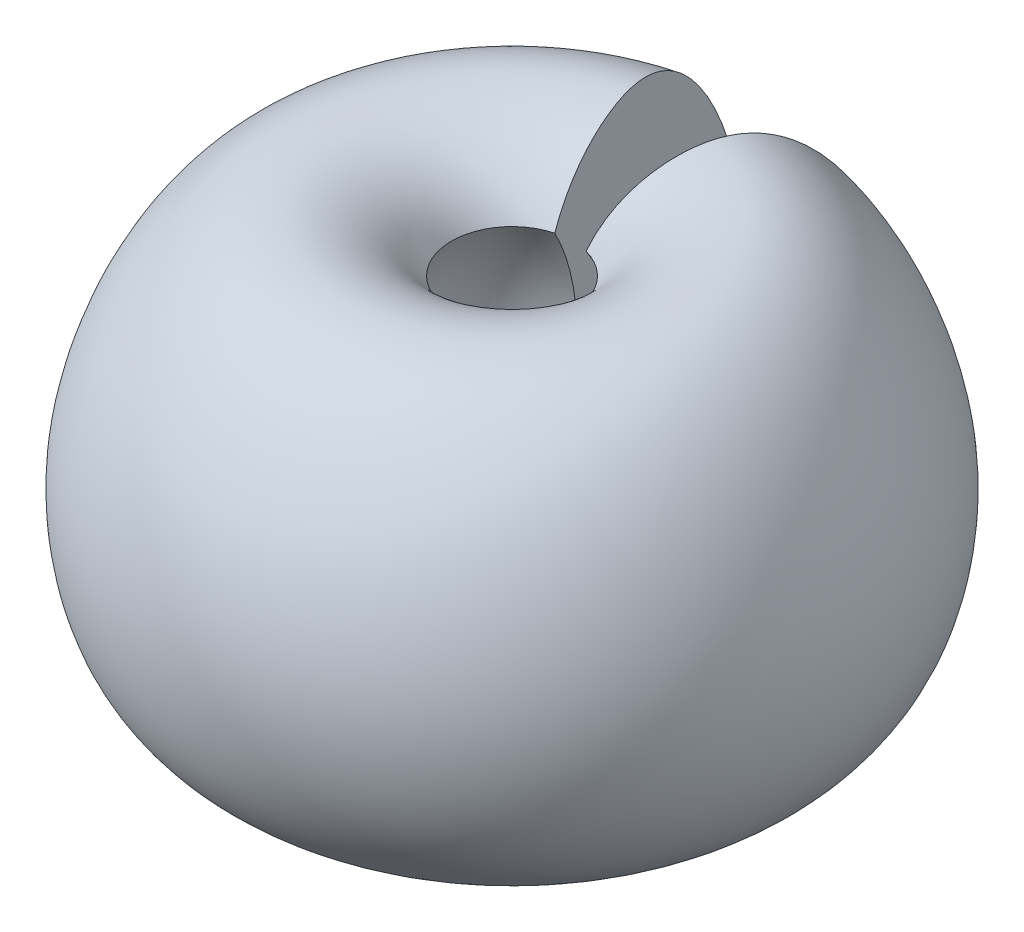
SolidWorks part; units mm, degrees
ref_plane "Alzado" through (0, 0, 0) normal (0, 0, 1) x (1, 0, 0)
ref_plane "Planta" through (0, 0, 0) normal (0, 1, 0) x (1, 0, 0)
ref_plane "Vista lateral" through (0, 0, 0) normal (1, 0, 0) x (0, 0, -1)
sketch "Croquis1" plane through (0, 0, 0) normal (0, 1, 0) x (1, 0, 0)
  line L0 (5348.5252, 0) -> (-5348.5252, 0)
  line L1 (0, 0) -> (0, 4683) construction
  line L2 (0, 0) -> (1212.0496, 4523.4306)
  line L3 (0, 0) -> (-1212.0496, 4523.4306)
  arc A0 (-1212.0496, 4523.4306) -> (1212.0496, 4523.4306) centre (0, 0) ccw
  point P4 (0, 0)
  dimension "D1" = 4683
  dimension "D2" = 15
  dimension "D3" = 15
sketch "Croquis2" plane through (0, 0, 0) normal (1, 0, 0) x (0, 0, -1)
  line L0 (-2174, 0) -> (-2174, -2800) construction
  line L1 (4523.4306, 0) -> (-4683, 0) construction
  line L2 (-859, 0) -> (-859, 2559) construction
  line L3 (-2331, 0) -> (-2331, 3409) construction
  line L4 (-859, 2559) -> (-1311.4686, 1000) construction
  line L5 (-1311.4686, 1000) -> (-859, -900) construction
  line L6 (-859, -900) -> (-424.6667, -2211.0837) construction
  line L10 (0, 0) -> (4523.4306, 0) construction
  arc A0 (-859, 2559) -> (-1311.4686, 1000) centre (1656.1841, 983.8581) ccw
  arc A1 (-1311.4686, 1000) -> (-859, -900) centre (-311.8117, 234.1839) ccw
  arc A2 (-859, -900) -> (-424.6667, -2211.0837) centre (979.3163, -1018.4905) ccw
  spline S0 degree 3 poles (-859, 2559) (-1168.7549, 3110.5904) (-1953.0979, 3467.4193) (-3655.0806, 3280.9651) (-4729.5399, 1125.1576) (-4610.4593, -2994.4531) (-1831.6032, -3259.9776) (-424.6667, -2211.0837) knots 0 0 0 0 0.088087 0.126077 0.3517 0.421493 1 1 1 1
  point P22 (-1311.4686, 907.4119)
  point P23 (-859, -835.5055)
  point P24 (0, 0)
  point P25 (0, 0)
  point P27 (0, 0)
  dimension "D1" = 3409
  dimension "D2" = 2800
  dimension "D3" = 2174
  dimension "D4" = 2331
  dimension "D5" = 2559
  dimension "D6" = 859
  dimension "D7" = 1000
  dimension "D8" = 1311.4686
  dimension "D9" = 900
  dimension "D10" = 859
sketch "Croquis3" plane through (0, 0, 0) normal (1, 0, 0) x (0, 0, -1)
  line L0 (0, 0) -> (0, 3051.3292) construction
  arc A0 (-859, -900) -> (-424.6667, -2211.0837) centre (979.3163, -1018.4905) ccw construction
  arc A1 (-859, 2559) -> (-1311.4686, 1000) centre (1656.1841, 983.8581) ccw construction
  arc A2 (-1311.4686, 1000) -> (-859, -900) centre (-311.8117, 234.1839) ccw construction
  arc A3 (-859, -900) -> (-424.6667, -2211.0837) centre (979.3163, -1018.4905) ccw
  arc A4 (-859, 2559) -> (-1311.4686, 1000) centre (1656.1841, 983.8581) ccw
  arc A5 (-1311.4686, 1000) -> (-859, -900) centre (-311.8117, 234.1839) ccw
  spline S0 degree 3 poles (-1070.1139, -346.2845) (94.6366, 2345.2209) (-1499.2138, 3517.1429) (-3655.0806, 3280.9651) (-4729.5399, 1125.1576) (-4567.7376, -4472.4166) (1485.5003, -2864.1338) (405.7519, 478.3327) knots -0.093791 -0.093791 -0.093791 -0.093791 0.088087 0.126077 0.3517 0.421493 1.313531 1.313531 1.313531 1.313531 only from (-859, 2559) to (-424.6667, -2211.0837) construction
  spline S1 degree 3 poles (-859, 2559) (-1168.7549, 3110.5904) (-1953.0979, 3467.4193) (-3655.0806, 3280.9651) (-4729.5399, 1125.1576) (-4610.4593, -2994.4531) (-1831.6032, -3259.9776) (-424.6667, -2211.0837) knots 0 0 0 0 0.088087 0.126077 0.3517 0.421493 1 1 1 1
revolve "Revolución1" add sketch "Croquis3" angle 330 mid plane about L0
sketch "Croquis4" plane through (0, 0, 0) normal (0, 1, 0) x (1, 0, 0)
  line L0 (0, 0) -> (0, -2225)
  line L1 (0, -4683.4263) -> (0, -424.6667) construction
  line L2 (150, -2225) -> (-150, -2225)
  point P8 (0, -2225)
  dimension "D1" = 2225
  dimension "D2" = 300
